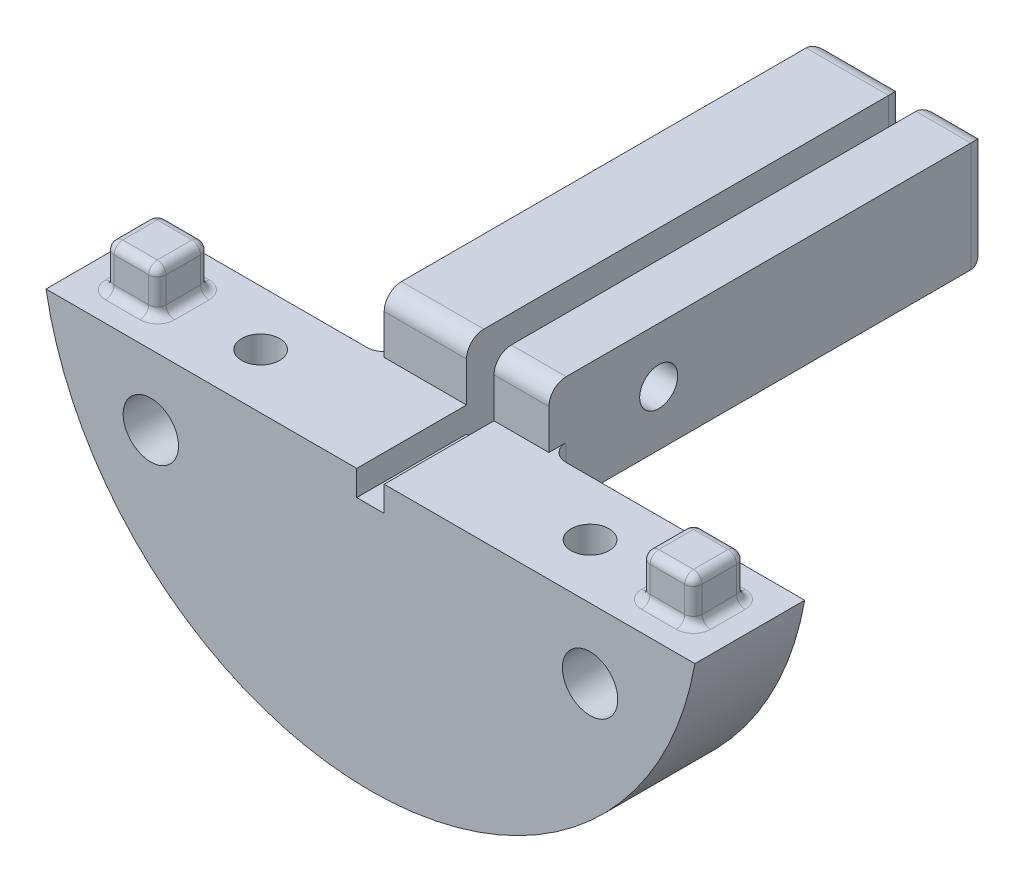
SolidWorks part; units mm, degrees
material "Polyetheretherketone (PEEK)"
ref_plane "Front" through (0, 0, 0) normal (0, 0, 1) x (1, 0, 0)
ref_plane "Top" through (0, 0, 0) normal (0, 1, 0) x (1, 0, 0)
ref_plane "Right" through (0, 0, 0) normal (1, 0, 0) x (0, 0, -1)
sketch "Sketch1" plane through (0, 0, 0) normal (0, 0, 1) x (1, 0, 0)
  line L0 (0, 0) -> (0, 14.0592) construction
  line L3 (0, 0) -> (-12.7, 0) construction
  line L8 (0, 0) -> (12.7, 0) construction
  circle A1 centre (0, 0) radius 19.05
  circle A5 centre (-12.7, 0) radius 0.5
  circle A6 centre (12.7, 0) radius 0.5
  circle A7 centre (0, 0) radius 0.5
  dimension "D1" = 12.7
  dimension "D2" = 38.1
  dimension "D6" = 1
extrude "Boss-Extrude1" add sketch "Sketch1" along normal blind 6.35
hole_wizard "M3 Clearance Hole1" positions "Sketch3" profile "Sketch2" hole size "M3" standard "Ansi Metric"
sketch "Sketch3" plane through (-15.666, 20.2196, 6.35) normal (0, 0, 1) x (1, 0, 0)
  line L0 (15.666, -20.2196) -> (2.966, -27.552) construction
  line L2 (15.666, -20.2196) -> (28.366, -27.552) construction
  line L4 (15.666, -20.2196) -> (15.666, -5.5549) construction
  point P0 (15.666, -5.5549)
  point P1 (2.966, -27.552)
  point P3 (28.366, -27.552)
  dimension "D1" = 120
  dimension "D2" = 120
  dimension "D3" = 25.4
sketch "Sketch2" plane through (0, 14.6647, 6.35) normal (1, 0, 0) x (0, -1, 0)
  line L0 (0, 0) -> (0, 30.6814)
  line L1 (0, 30.6814) -> (1.6, 29.72)
  line L2 (1.6, 29.72) -> (1.6, 0)
  line L5 (1.6, 0) -> (0, 0)
  line L10 (0, 30.6814) -> (-1.6, 29.72) construction
  line L11 (0, -6.35) -> (0, 107.95) construction
  dimension "Hole Dia." = 3.2
  dimension "Hole Depth" = 29.72
  dimension "Drill Angle" = 118
sketch "Sketch4" plane through (0, 0, 0) normal (0, 0, -1) x (-1, 0, 0)
  line L0 (0, -3.175) -> (-18.8043, -3.175) construction
  line L1 (0, -3.175) -> (0, 19.05) construction
  line L2 (18.8043, -3.05) -> (-18.8043, -3.05)
  line L3 (-18.8043, -3.05) -> (-18.8043, -3.3)
  line L4 (18.8043, -3.3) -> (-18.8043, -3.3)
  line L5 (18.8043, -3.05) -> (18.8043, -3.3)
  circle A0 centre (0, 0) radius 19.05 construction
  point P12 (0, -3.3)
  point P13 (0, -3.05)
  dimension "D1" = 0.125
  dimension "D2" = 3.175
extrude "Cut-Extrude1" cut sketch "Sketch4" against normal through all
ref_plane "Plane1" through (0, 19.05, 0) normal (0, 1, 0) x (-1, 0, 0)
hole_wizard "CBORE for M2 SHCS1" positions "Sketch10" profile "Sketch9" counterbore size "M2" standard "Ansi Metric" end condition through all
sketch "Sketch10" plane through (0, 19.05, 0) normal (0, 1, 0) x (-1, 0, 0)
  line L0 (0, 0) -> (0, 6.35) construction
  line L1 (-19.05, 0) -> (19.05, 0) construction
  line L2 (19.05, 6.35) -> (-19.05, 6.35) construction
  line L4 (0, 3.175) -> (9.525, 3.175) construction
  line L6 (0, 3.175) -> (-9.525, 3.175) construction
  point P2 (9.525, 3.175)
  point P4 (-9.525, 3.175)
  dimension "D1" = 9.525
sketch "Sketch9" plane through (-9.525, 19.05, 3.175) normal (1, 0, 0) x (0, 0, 1)
  line L0 (0, 0) -> (0, 38.1)
  line L1 (0, 38.1) -> (1.1, 38.1)
  line L3 (1.1, 38.1) -> (1.1, 2)
  line L4 (1.1, 2) -> (2.2, 2)
  line L5 (2.2, 2) -> (2.2, 0)
  line L7 (2.2, 0) -> (0, 0)
  line L11 (0, -6.35) -> (0, 107.95) construction
  dimension "Thru Hole Dia." = 2.2
  dimension "Thru Hole Depth" = 38.1
  dimension "C'Bore Dia." = 4.4
  dimension "C'Bore Depth" = 2
ref_plane "Plane2" through (0, -19.05, 0) normal (0, -1, 0) x (1, 0, 0)
sketch "Sketch11" plane through (0, -19.05, 0) normal (0, -1, 0) x (1, 0, 0)
  line L0 (-9.525, 3.175) -> (-7.2156, 3.175) construction
  line L1 (-9.525, 3.175) -> (-11.8344, 3.175) construction
  line L2 (-9.525, 3.175) -> (-10.6797, 5.175) construction
  line L3 (-9.525, 3.175) -> (-10.6797, 1.175) construction
  line L4 (-10.6797, 5.175) -> (-11.8344, 3.175)
  line L5 (-11.8344, 3.175) -> (-10.6797, 1.175)
  line L6 (-10.6797, 1.175) -> (-8.3703, 1.175)
  line L7 (-8.3703, 1.175) -> (-7.2156, 3.175)
  line L8 (-7.2156, 3.175) -> (-8.3703, 5.175)
  line L9 (-8.3703, 5.175) -> (-10.6797, 5.175)
  line L10 (-9.525, 3.175) -> (-8.3703, 5.175) construction
  line L11 (-9.525, 3.175) -> (-8.3703, 1.175) construction
  line L12 (8.3703, 5.175) -> (7.2156, 3.175)
  line L13 (7.2156, 3.175) -> (8.3703, 1.175)
  line L14 (8.3703, 1.175) -> (10.6797, 1.175)
  line L15 (10.6797, 1.175) -> (11.8344, 3.175)
  line L16 (11.8344, 3.175) -> (10.6797, 5.175)
  line L17 (10.6797, 5.175) -> (8.3703, 5.175)
  line L18 (9.525, 3.175) -> (11.8344, 3.175) construction
  line L19 (9.525, 3.175) -> (7.2156, 3.175) construction
  line L20 (9.525, 3.175) -> (8.3703, 5.175) construction
  line L21 (9.525, 3.175) -> (8.3703, 1.175) construction
  line L22 (9.525, 3.175) -> (10.6797, 5.175) construction
  line L23 (9.525, 3.175) -> (10.6797, 1.175) construction
  dimension "D1" = 60
  dimension "D2" = 60
  dimension "D3" = 4
  dimension "D4" = 2
extrude "Cut-Extrude2" cut sketch "Sketch11" against normal blind 10
fillet "Fillet1" radius 2.3813 6 edges at (0.5, 0, 0) (0.5, 0, 6.35) (13.2, 0, 0) (-12.2, 0, 6.35) (-12.2, 0, 0) (13.2, 0, 6.35)
sketch "Sketch12" plane through (0, 0, 0) normal (0, 0, 1) x (1, 0, 0)
  line L0 (-18.8043, -3.05) -> (18.8043, -3.05) construction
  line L1 (-27.8472, -3.05) -> (27.9327, -3.05)
  line L2 (-27.8472, -3.05) -> (-27.8472, 24.7859)
  line L3 (-27.8472, 24.7859) -> (27.9327, 24.7859)
  line L4 (27.9327, -3.05) -> (27.9327, 24.7859)
extrude "Cut-Extrude3" cut sketch "Sketch12" along normal through all
sketch "Sketch13" plane through (0, -3.3, 0) normal (0, 1, 0) x (1, 0, 0)
  line L0 (-18.762, -3.175) -> (18.762, -3.175) construction
  line L2 (18.762, 0) -> (18.762, -6.35) construction
  line L3 (-17, -4.675) -> (-17, -1.675)
  line L4 (-17, -1.675) -> (-14, -1.675)
  line L5 (-14, -1.675) -> (-14, -4.675)
  line L6 (0, -3.175) -> (0, 0) construction
  line L7 (-17, -4.675) -> (-14, -4.675)
  line L8 (17, -4.675) -> (14, -4.675)
  line L9 (14, -1.675) -> (14, -4.675)
  line L10 (17, -1.675) -> (14, -1.675)
  line L11 (17, -4.675) -> (17, -1.675)
  point P14 (-14, -3.175)
  point P15 (-17, -3.175)
  point P19 (17, -3.175)
  point P20 (14, -3.175)
  dimension "D1" = 3
  dimension "D2" = 14
  dimension "D3" = 3
extrude "Boss-Extrude2" add sketch "Sketch13" along normal blind 2.5
fillet "Fillet2" radius 0.5 24 edges at (-14, -3.3, 3.175) (-14, -2.05, 1.675) (-15.5, -3.3, 1.675) (-17, -2.05, 1.675) (-17, -3.3, 3.175) (-17, -2.05, 4.675) (-14, -2.05, 4.675) (-15.5, -3.3, 4.675) (-14, -0.8, 3.175) (-15.5, -0.8, 4.675) (-17, -0.8, 3.175) (-15.5, -0.8, 1.675) (15.5, -3.3, 4.675) (14, -2.05, 4.675) (14, -3.3, 3.175) (17, -2.05, 4.675) (17, -3.3, 3.175) (17, -2.05, 1.675) (14, -2.05, 1.675) (15.5, -3.3, 1.675) (15.5, -0.8, 4.675) (14, -0.8, 3.175) (15.5, -0.8, 1.675) (17, -0.8, 3.175)
sketch "Sketch14" plane through (0, 0, 0) normal (0, 0, -1) x (-1, 0, 0)
  line L0 (0, 0) -> (0, -14.5882) construction
  line L1 (-18.762, -3.3) -> (18.762, -3.3) construction
  line L2 (-0.7937, -3.3) -> (0.7938, -3.3)
  line L3 (-0.7937, -3.3) -> (-0.7937, -4.7625)
  line L4 (-0.7937, -4.7625) -> (0.7938, -4.7625)
  line L5 (0.7938, -3.3) -> (0.7938, -4.7625)
  point P10 (0, -4.7625)
  point P11 (0, -3.3)
  dimension "D1" = 4.7625
  dimension "D2" = 1.5875
extrude "Cut-Extrude4" cut sketch "Sketch14" against normal through all
sketch "Sketch15" plane through (0, 0, 0) normal (0, 0, -1) x (-1, 0, 0)
  line L0 (-0.7938, 0) -> (0.7938, 0) construction
  line L1 (-0.7938, -6.35) -> (-3.9688, -6.35)
  line L2 (-0.7938, -6.35) -> (-0.7938, 0)
  line L3 (-0.7938, 0) -> (-3.9688, 0)
  line L4 (-3.9688, -6.35) -> (-3.9688, 0)
  line L5 (0.7938, -6.35) -> (5.5563, -6.35)
  line L6 (0.7938, -6.35) -> (0.7938, 0)
  line L7 (0.7938, 0) -> (5.5563, 0)
  line L8 (5.5563, -6.35) -> (5.5563, 0)
  dimension "D1" = 6.35
  dimension "D2" = 3.175
  dimension "D3" = 4.7625
extrude "Boss-Extrude3" add sketch "Sketch15" along normal blind 25.4
hole_wizard "M2 Clearance Hole1" positions "Sketch17" profile "Sketch16" hole size "M2" standard "ANSI Metric"
sketch "Sketch17" plane through (-5.5563, 0, 0) normal (-1, 0, 0) x (0, 0, 1)
  line L1 (0, -3.175) -> (-6.35, -3.175) construction
  line L2 (-6.35, -3.175) -> (-6.35, 0) construction
  line L3 (-25.4, 0) -> (0, 0) construction
  line L5 (-6.35, -3.175) -> (-6.35, -6.35) construction
  line L6 (-25.4, -6.35) -> (0, -6.35) construction
  point P0 (-6.35, -3.175)
  dimension "D1" = 6.35
sketch "Sketch16" plane through (-5.5563, -3.175, -6.35) normal (0, 1, 0) x (0, 0, 1)
  line L0 (0, 0) -> (0, 29.0109)
  line L1 (0, 29.0109) -> (1.1, 28.35)
  line L2 (1.1, 28.35) -> (1.1, 0)
  line L5 (1.1, 0) -> (0, 0)
  line L10 (0, 29.0109) -> (-1.1, 28.35) construction
  line L11 (0, -6.35) -> (0, 107.95) construction
  dimension "Hole Dia." = 2.2
  dimension "Hole Depth" = 28.35
  dimension "Drill Angle" = 118
sketch "Sketch18" plane through (-5.5563, 0, 0) normal (-1, 0, 0) x (0, 0, 1)
  line L0 (-7.5047, -1.175) -> (-5.1953, -1.175)
  line L1 (-5.1953, -1.175) -> (-4.0406, -3.175)
  line L2 (-4.0406, -3.175) -> (-5.1953, -5.175)
  line L3 (-5.1953, -5.175) -> (-7.5047, -5.175)
  line L4 (-7.5047, -5.175) -> (-8.6594, -3.175)
  line L5 (-8.6594, -3.175) -> (-7.5047, -1.175)
  line L6 (-7.5047, -1.175) -> (-6.35, -3.175) construction
  line L8 (-8.6594, -3.175) -> (-6.35, -3.175) construction
  line L9 (-6.35, -3.175) -> (-4.0406, -3.175) construction
  dimension "D1" = 4
extrude "Cut-Extrude5" cut sketch "Sketch18" against normal blind 2.5
fillet "Fillet3" radius 1 12 edges at (2.3813, -6.35, -25.4) (3.9688, -3.175, -25.4) (2.3813, 0, -25.4) (0.7938, -3.175, -25.4) (-3.175, 0, -25.4) (-5.5563, -3.175, -25.4) (-3.175, -6.35, -25.4) (-0.7938, -3.175, -25.4) (3.9688, -4.825, 0) (2.3813, -6.35, 0) (-3.175, -6.35, 0) (-5.5563, -4.825, 0)
fillet "Fillet4" radius 1 2 edges at (2.3813, 0, 0) (-3.175, 0, 0)
